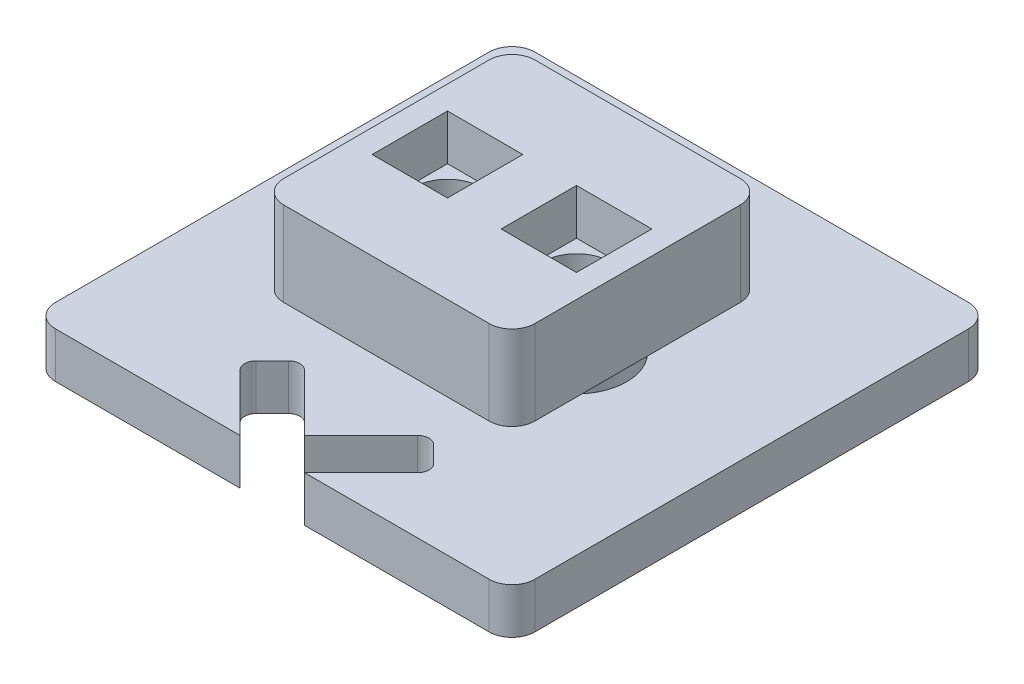
SolidWorks part; units mm, degrees
ref_plane "Front Plane" through (0, 0, 0) normal (0, 0, 1) x (1, 0, 0)
ref_plane "Top Plane" through (0, 0, 0) normal (0, 1, 0) x (1, 0, 0)
ref_plane "Right Plane" through (0, 0, 0) normal (1, 0, 0) x (0, 0, -1)
sketch "Sketch1" plane through (0, 0, 0) normal (0, 1, 0) x (1, 0, 0)
  line L1 (-5.5, -5.5) -> (5.5, -5.5)
  line L2 (-5.5, -5.5) -> (-5.5, 5.5)
  line L3 (-5.5, 5.5) -> (5.5, 5.5)
  line L4 (5.5, -5.5) -> (5.5, 5.5)
  line L5 (-5.5, -5.5) -> (5.5, 5.5) construction
  line L6 (-5.5, 5.5) -> (5.5, -5.5) construction
  point P0 (0, 0)
  dimension "D1" = 11
  dimension "D2" = 11
extrude "Boss-Extrude1" add sketch "Sketch1" along normal blind 3.7
fillet "Fillet1" radius 1 4 edges at (-5.5, 1.85, -5.5) (-5.5, 1.85, 5.5) (5.5, 1.85, -5.5) (5.5, 1.85, 5.5)
sketch "Sketch2" plane through (0, 3.7, 0) normal (0, 1, 0) x (1, 0, 0)
  line L0 (-2.825, 0) -> (2.825, 0) construction
  line L2 (-4.475, -1.65) -> (-1.175, -1.65)
  line L3 (-4.475, -1.65) -> (-4.475, 1.65)
  line L4 (-4.475, 1.65) -> (-1.175, 1.65)
  line L5 (-1.175, -1.65) -> (-1.175, 1.65)
  line L6 (-4.475, -1.65) -> (-1.175, 1.65) construction
  line L7 (-4.475, 1.65) -> (-1.175, -1.65) construction
  line L8 (1.175, -1.65) -> (4.475, -1.65)
  line L9 (1.175, -1.65) -> (1.175, 1.65)
  line L10 (1.175, 1.65) -> (4.475, 1.65)
  line L11 (4.475, -1.65) -> (4.475, 1.65)
  line L12 (1.175, -1.65) -> (4.475, 1.65) construction
  line L13 (1.175, 1.65) -> (4.475, -1.65) construction
  point P4 (0, 0)
  dimension "D1" = 3.3
  dimension "D2" = 3.3
  dimension "D3" = 3.3
  dimension "D4" = 3.3
  dimension "D5" = 5.65
extrude "Cut-Extrude1" cut sketch "Sketch2" against normal blind 2
sketch "Sketch4" plane through (0, 0, 0) normal (0, -1, 0) x (-1, 0, 0)
  line L0 (2.825, 0) -> (-2.825, 0) construction
  circle A0 centre (2.825, 0) radius 2.2
  circle A1 centre (-2.825, 0) radius 2.2
  point P4 (0, 0)
  point P8 (0, 0)
  dimension "D1" = 5.65
  dimension "D2" = 4.4
  dimension "D3" = 4.4
extrude "Boss-Extrude2" add sketch "Sketch4" along normal blind 3
sketch "Sketch5" plane through (0, -3, 0) normal (0, -1, 0) x (-1, 0, 0)
  line L1 (9.5, 10.5) -> (-9.5, 10.5)
  line L2 (10.5, 9.5) -> (10.5, -9.5)
  line L3 (9.5, -10.5) -> (-9.5, -10.5)
  line L4 (-10.5, 9.5) -> (-10.5, -9.5)
  line L5 (10.5, 10.5) -> (-10.5, -10.5) construction
  line L6 (10.5, -10.5) -> (-10.5, 10.5) construction
  arc A0 (10.5, -9.5) -> (9.5, -10.5) centre (9.5, -9.5) cw
  arc A1 (-10.5, -9.5) -> (-9.5, -10.5) centre (-9.5, -9.5) ccw
  arc A2 (-9.5, 10.5) -> (-10.5, 9.5) centre (-9.5, 9.5) ccw
  arc A3 (9.5, 10.5) -> (10.5, 9.5) centre (9.5, 9.5) cw
  point P0 (0, 0)
  dimension "D3" = 1
  dimension "D1" = 21
  dimension "D2" = 21
extrude "Boss-Extrude3" add sketch "Sketch5" against normal blind 2
sketch "Sketch3" plane through (0, 3.7, 0) normal (0, 1, 0) x (1, 0, 0)
  line L0 (-2.825, 0) -> (2.825, 0) construction
  circle A0 centre (-2.825, 0) radius 1.5
  circle A1 centre (2.825, 0) radius 1.5
  point P4 (0, 0)
  point P5 (0, 0)
  point P8 (0, 0)
  dimension "D2" = 3
  dimension "D3" = 3
  dimension "D1" = 5.65
extrude "Cut-Extrude2" cut sketch "Sketch3" against normal through all
sketch "Sketch7" plane through (0, -1, 0) normal (0, 1, 0) x (1, 0, 0)
  line L0 (9.5, -10.5) -> (-9.5, -10.5) construction
  line L1 (2.8284, -14.7426) -> (4.2426, -13.3284)
  line L2 (2.8284, -14.7426) -> (-3.8891, -8.0251)
  line L3 (-3.8891, -7.318) -> (-3.182, -6.6109)
  line L4 (4.2426, -13.3284) -> (-2.4749, -6.6109)
  line L5 (2.8284, -14.7426) -> (-2.8284, -6.2574) construction
  line L6 (-4.2426, -7.6716) -> (4.2426, -13.3284) construction
  line L8 (-4.2426, -13.3284) -> (-2.8284, -14.7426)
  line L9 (-4.2426, -13.3284) -> (2.4749, -6.6109)
  line L10 (3.182, -6.6109) -> (3.8891, -7.318)
  line L11 (-2.8284, -14.7426) -> (3.8891, -8.0251)
  line L12 (-4.2426, -13.3284) -> (4.2426, -7.6716) construction
  line L13 (2.8284, -6.2574) -> (-2.8284, -14.7426) construction
  arc A0 (-2.4749, -6.6109) -> (-3.182, -6.6109) centre (-2.8284, -6.9645) ccw
  arc A1 (3.8891, -7.318) -> (3.8891, -8.0251) centre (3.5355, -7.6716) cw
  arc A2 (3.182, -6.6109) -> (2.4749, -6.6109) centre (2.8284, -6.9645) ccw
  arc A3 (-3.8891, -7.318) -> (-3.8891, -8.0251) centre (-3.5355, -7.6716) ccw
  point P0 (0, -10.5)
  point P7 (0, -10.5)
  point P12 (-1.4142, -10.5)
  point P13 (1.4142, -10.5)
  line M12 (-9.5, -10.5) -> (9.5, -10.5)
  dimension "D7" = 0.5
  dimension "D8" = 0.5
  dimension "D1" = 2
  dimension "D2" = 45
  dimension "D3" = 2
  dimension "D4" = 45
  dimension "D5" = 4
  dimension "D6" = 4
extrude "Cut-Extrude3" cut sketch "Sketch7" against normal through all contours L10 A2 L9 L4 L11 A1 | L3 A3 L2 L9 L4 A0 | L9 L4 M12
equation "\"D2@Sketch2\"=\"D1@Sketch2\""
equation "\"D3@Sketch2\"=\"D1@Sketch2\""
equation "\"D4@Sketch2\"=\"D1@Sketch2\""
equation "\"D2@Sketch1\"=\"D1@Sketch1\""
equation "\"D3@Sketch3\"=\"D2@Sketch3\""
equation "\"D3@Sketch4\"=\"D2@Sketch4\""
equation "\"D2@Sketch5\"=\"D1@Sketch5\""
equation "\"D3@Sketch7\"=\"D1@Sketch7\""
equation "\"D6@Sketch7\"=\"D5@Sketch7\""
